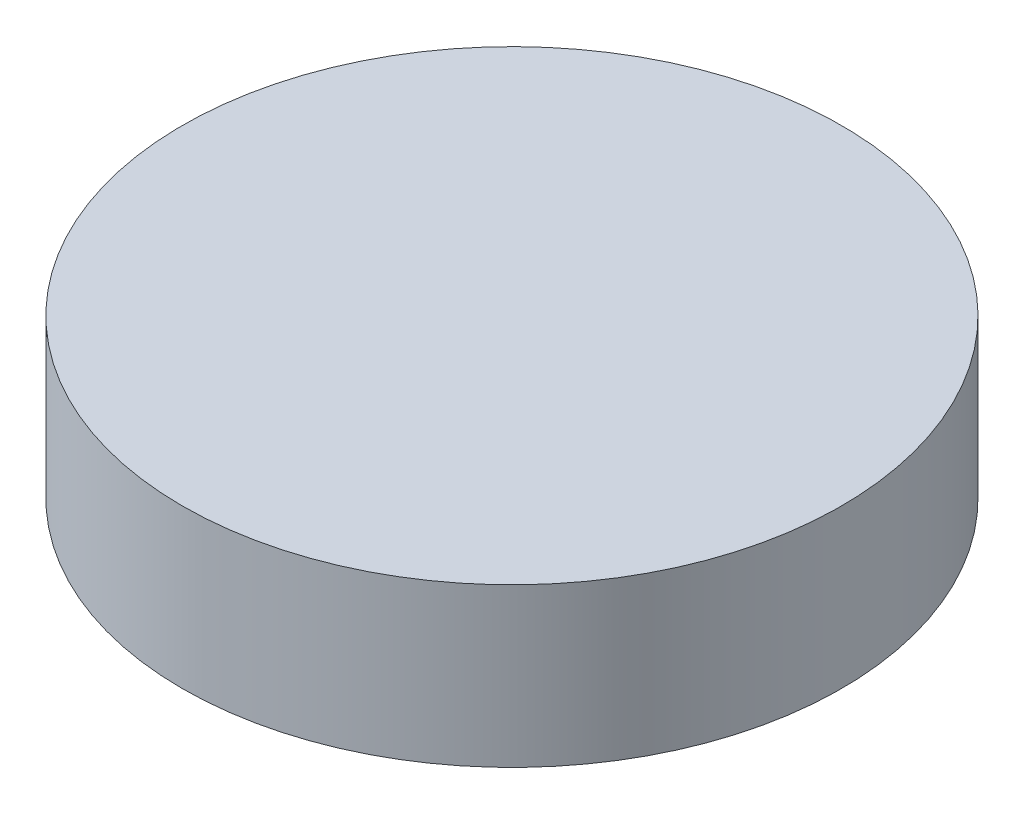
SolidWorks part; units mm, degrees
ref_plane "Front Plane" through (0, 0, 0) normal (0, 0, 1) x (1, 0, 0)
ref_plane "Top Plane" through (0, 0, 0) normal (0, 1, 0) x (1, 0, 0)
ref_plane "Right Plane" through (0, 0, 0) normal (1, 0, 0) x (0, 0, -1)
other "Configuration Table"
sketch "Sketch1" plane through (0, 0, 0) normal (0, 1, 0) x (1, 0, 0)
  circle A0 centre (50, 50) radius 25
extrude "PACK_ayar_ayagi_1" add sketch "Sketch1" along normal blind 12 separate body
